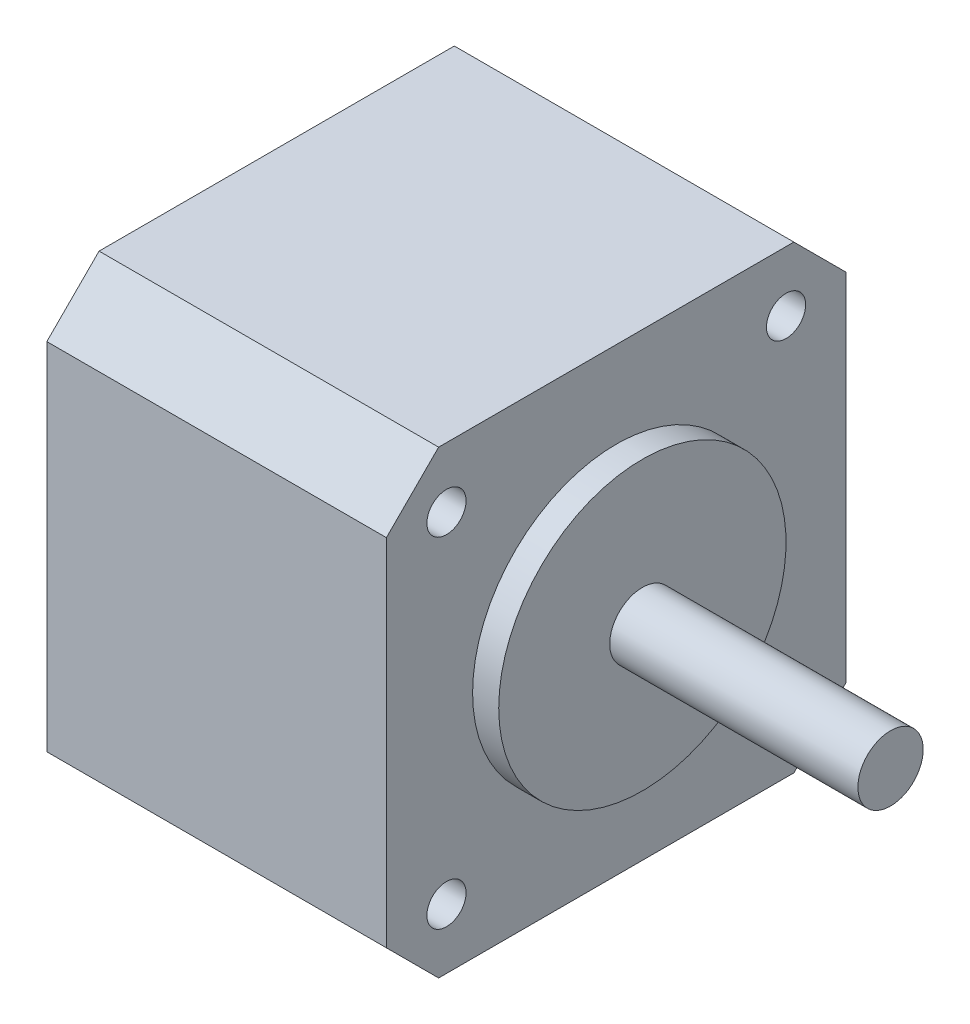
SolidWorks part; units mm, degrees
ref_plane "Front Plane" through (0, 0, 0) normal (0, 0, 1) x (1, 0, 0)
ref_plane "Top Plane" through (0, 0, 0) normal (0, 1, 0) x (1, 0, 0)
ref_plane "Right Plane" through (0, 0, 0) normal (1, 0, 0) x (0, 0, -1)
sketch "Sketch1" plane through (0, 0, 0) normal (1, 0, 0) x (0, 0, -1)
  circle A0 centre (0, 0) radius 2.5
  dimension "D1" = 5
extrude "Boss-Extrude1" add sketch "Sketch1" against normal blind 19
sketch "Sketch2" plane through (-19, 0, 0) normal (-1, 0, 0) x (0, 0, 1)
  circle A0 centre (0, 0) radius 11
  dimension "D1" = 22
extrude "Boss-Extrude2" add sketch "Sketch2" along normal blind 2
sketch "Sketch3" plane through (-21, 0, 0) normal (-1, 0, 0) x (0, 0, 1)
  line L1 (-17.6, -17.6) -> (17.6, -17.6)
  line L2 (-17.6, -17.6) -> (-17.6, 17.6)
  line L3 (-17.6, 17.6) -> (17.6, 17.6)
  line L4 (17.6, -17.6) -> (17.6, 17.6)
  line L5 (-17.6, -17.6) -> (17.6, 17.6) construction
  line L6 (-17.6, 17.6) -> (17.6, -17.6) construction
  circle A0 centre (-13, 13) radius 1.5
  circle A1 centre (13, 13) radius 1.5
  circle A2 centre (13, -13) radius 1.5
  circle A3 centre (-13, -13) radius 1.5
  point P0 (0, 0)
  point P17 (0, 0)
  dimension "D4" = 3
  dimension "D1" = 35.2
  dimension "D2" = 35.2
  dimension "D5" = 26
  dimension "D3" = 4
extrude "Boss-Extrude3" add sketch "Sketch3" along normal blind 4
sketch "Sketch4" plane through (-25, 0, 0) normal (-1, 0, 0) x (0, 0, 1)
  line L0 (-17.6, -17.6) -> (17.6, -17.6) construction
  line L1 (17.6, -17.6) -> (17.6, 17.6) construction
  line L2 (-17.6, 17.6) -> (-17.6, -17.6) construction
  line L3 (17.6, 17.6) -> (-17.6, 17.6) construction
  line L4 (-17.6, -17.6) -> (17.6, -17.6)
  line L5 (17.6, -17.6) -> (17.6, 17.6)
  line L6 (-17.6, 17.6) -> (-17.6, -17.6)
  line L7 (17.6, 17.6) -> (-17.6, 17.6)
extrude "Boss-Extrude4" add sketch "Sketch4" along normal blind 22
chamfer "Chamfer1" distance 4 angle 45 4 edges at (-34, -17.6, -17.6) (-34, -17.6, 17.6) (-34, 17.6, -17.6) (-34, 17.6, 17.6)
sketch "Sketch5" plane through (-47, 0, 0) normal (-1, 0, 0) x (0, 0, 1)
  circle A0 centre (0, 0) radius 24.8902 construction
  dimension "D1" = 49.7803
